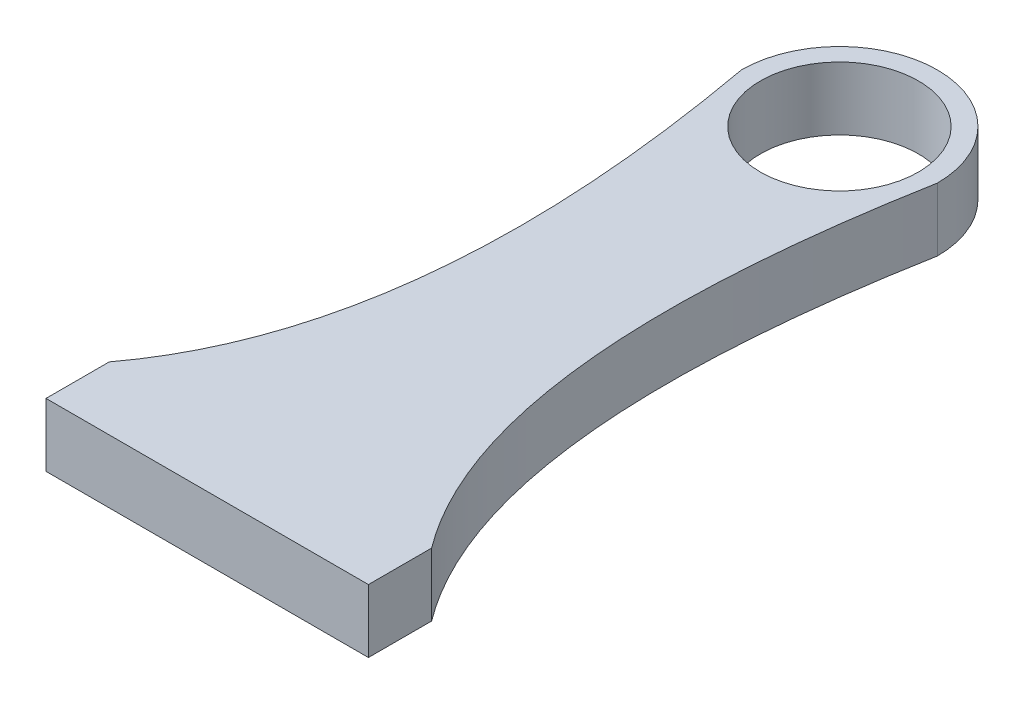
SolidWorks part; units mm, degrees
material "3.1355 (EN-AW 2024)"
ref_plane "Спереди" through (0, 0, 0) normal (0, 0, 1) x (1, 0, 0)
ref_plane "Сверху" through (0, 0, 0) normal (0, 1, 0) x (1, 0, 0)
ref_plane "Справа" through (0, 0, 0) normal (1, 0, 0) x (0, 0, -1)
sketch "Эскиз1" plane through (0, 0, 0) normal (0, 1, 0) x (1, 0, 0)
  line L0 (0, 0) -> (0, -100) construction
  line L1 (-15.5, 0) -> (-15.5, -100)
  line L2 (-15.5, -100) -> (15.5, -100)
  line L3 (15.5, -100) -> (15.5, 0)
  circle A0 centre (0, 0) radius 12.5
  arc A1 (15.5, 0) -> (-15.5, 0) centre (0, 0) ccw
  dimension "D1" = 25
  dimension "D2" = 31
  dimension "D3" = 100
extrude "Бобышка-Вытянуть1" add sketch "Эскиз1" along normal blind 10
sketch "Эскиз2" plane through (0, 10, 0) normal (0, 1, 0) x (1, 0, 0)
  line L0 (-15.5, -100) -> (15.5, -100) construction
  line L1 (-25.5, -90) -> (25.5, -90)
  line L2 (-25.5, -90) -> (-25.5, -100)
  line L3 (-25.5, -100) -> (25.5, -100)
  line L4 (25.5, -90) -> (25.5, -100)
  line L5 (-25.5, -90) -> (25.5, -100) construction
  line L6 (-25.5, -100) -> (25.5, -90) construction
  point P0 (0, -95)
  point P5 (0, -100)
  point P8 (0, 0)
  dimension "D1" = 51
  dimension "D2" = 10
extrude "Бобышка-Вытянуть2" add sketch "Эскиз2" against normal through all
sketch "Эскиз4" plane through (0, 10, 0) normal (0, 1, 0) x (1, 0, 0)
  line L0 (-25.5, -90) -> (-15.5, 0)
  line L1 (-15.5, 0) -> (-15.5, -90)
  line L2 (-15.5, -90) -> (-25.5, -90)
  line L3 (0, -12.5) -> (0, -100) construction
  line L4 (15.5, -90) -> (25.5, -90)
  line L5 (15.5, 0) -> (15.5, -90)
  line L6 (25.5, -90) -> (15.5, 0)
  line L7 (-25.5, -100) -> (25.5, -100) construction
extrude "Бобышка-Вытянуть3" add sketch "Эскиз4" against normal blind 10
sketch "Эскиз3" plane through (0, 10, 0) normal (0, 1, 0) x (1, 0, 0)
  line L0 (0, -12.5) -> (0, -100) construction
  line L1 (-25.5, -100) -> (25.5, -100) construction
  line L2 (-25.5, -100) -> (-25.5, -90) construction
  line L3 (0, 0) -> (-15.5, 0) construction
  line L4 (-15.5, 0) -> (-25.5, -90)
  line L5 (15.5, 0) -> (25.5, -90)
  circle A0 centre (0, 0) radius 12.5 construction
  arc A1 (15.5, 0) -> (-15.5, 0) centre (0, 0) ccw construction
  spline S0 degree 2 poles (-15.5, 0) (-4.2368, -61.6464) (-25.5, -90) knots 0 0 0 1 1 1
  spline S1 degree 2 poles (15.5, 0) (4.2368, -61.6464) (25.5, -90) knots 0 0 0 1 1 1
  dimension "D1" = 10
extrude "Вырез-Вытянуть2" cut sketch "Эскиз3" against normal blind 10
equation "\"D2@Эскиз1\"=\"D1@Эскиз1\"+6"
